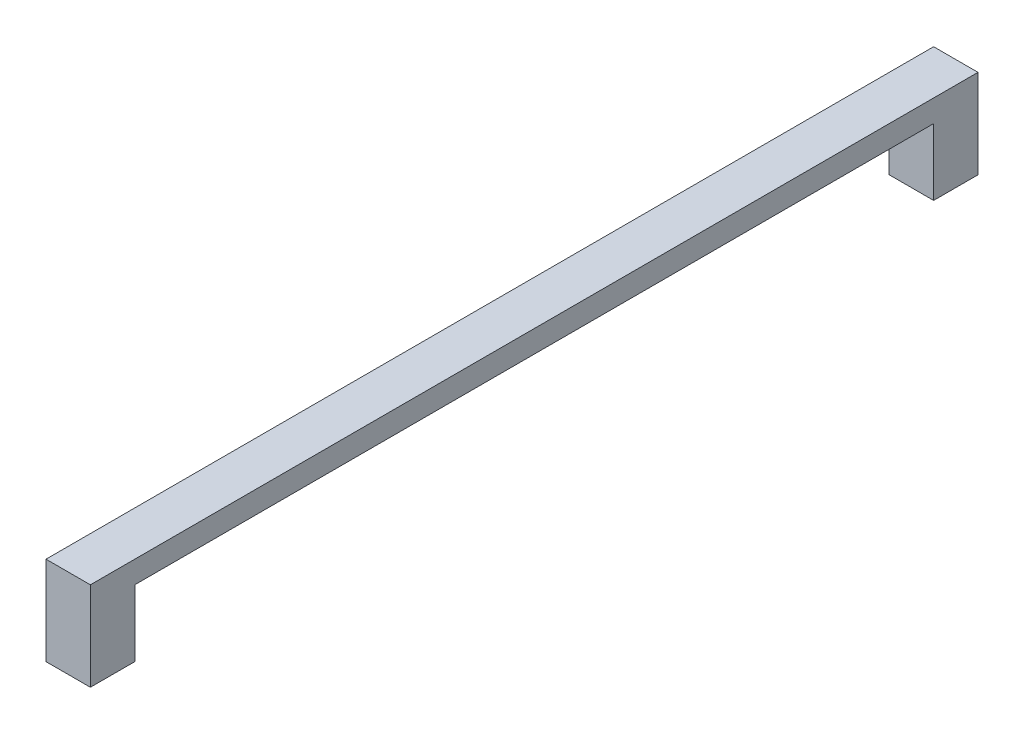
SolidWorks part; units mm, degrees
ref_plane "Front Plane" through (0, 0, 0) normal (0, 0, 1) x (1, 0, 0)
ref_plane "Top Plane" through (0, 0, 0) normal (0, 1, 0) x (1, 0, 0)
ref_plane "Right Plane" through (0, 0, 0) normal (1, 0, 0) x (0, 0, -1)
sketch "Sketch2" plane through (0, 0, 0) normal (1, 0, 0) x (0, 0, -1)
  line L0 (856.5374, 0) -> (856.5374, -4.8908) construction
  line L1 (-43.4626, 120.2885) -> (1756.5374, 120.2885)
  line L2 (-143.4626, 120.2885) -> (-143.4626, 170.2885)
  line L3 (-143.4626, 170.2885) -> (1856.5374, 170.2885)
  line L5 (1856.5374, -29.7115) -> (1756.5374, -29.7115)
  line L6 (-143.4626, 170.2885) -> (-50.9762, 60.5082) construction
  line L7 (-143.4626, 120.2885) -> (-143.4626, -29.7115)
  line L8 (-143.4626, -29.7115) -> (-43.4626, -29.7115)
  line L9 (-43.4626, -29.7115) -> (-43.4626, 120.2885)
  line L10 (1756.5374, -29.7115) -> (1756.5374, 120.2885)
  line L11 (1856.5374, 120.2885) -> (1856.5374, 170.2885)
  line L12 (1856.5374, 120.2885) -> (1856.5374, -29.7115)
  point P0 (0, 0)
  point P4 (856.5374, 120.2885)
  point P17 (856.5374, 170.2885)
  dimension "D1" = 100
  dimension "D2" = 2000
  dimension "D3" = 150
  dimension "D4" = 50
extrude "Boss-Extrude1" add sketch "Sketch2" along normal blind 100
